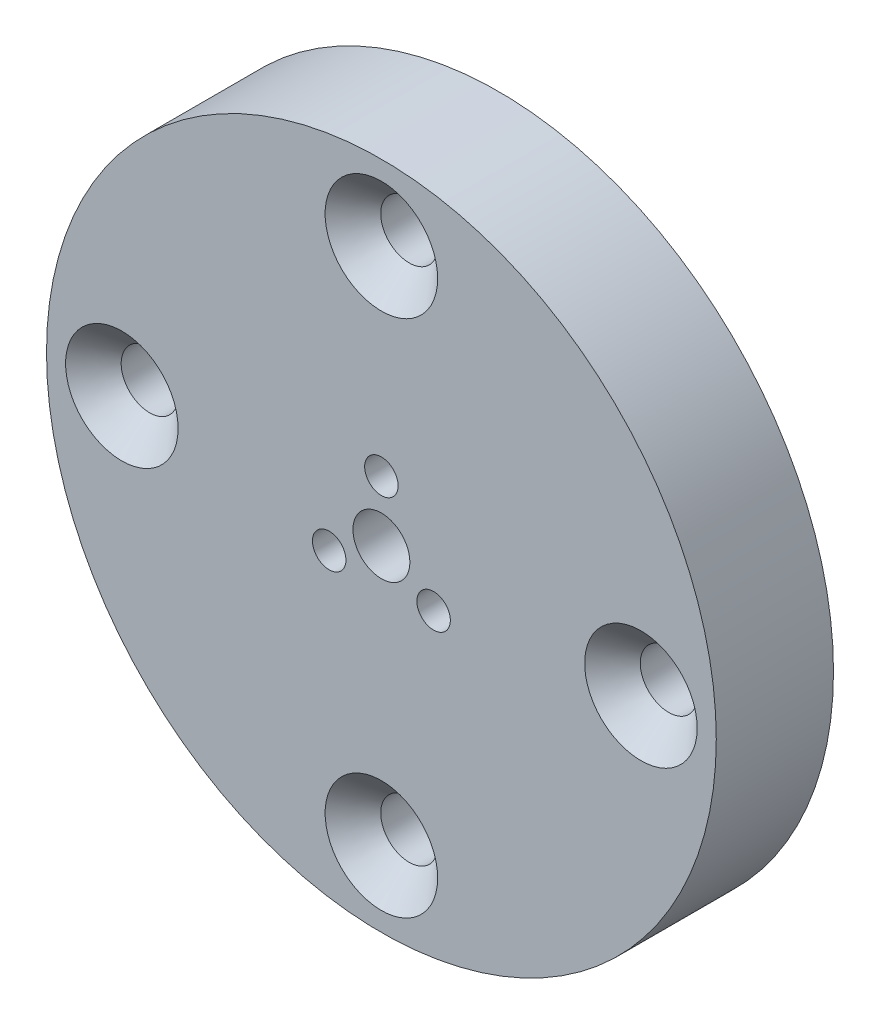
SolidWorks part; units mm, degrees
material "7075-O (SS)"
ref_plane "Front" through (0, 0, 0) normal (0, 0, 1) x (1, 0, 0)
ref_plane "Top" through (0, 0, 0) normal (0, 1, 0) x (1, 0, 0)
ref_plane "Right" through (0, 0, 0) normal (1, 0, 0) x (0, 0, -1)
sketch "Croquis1" plane through (0, 0, 0) normal (0, 0, 1) x (1, 0, 0)
  line L0 (0, -2.75) -> (0, 2.75) construction
  line L1 (2.75, 0) -> (-2.75, 0) construction
  circle A0 centre (0, 0) radius 20
  circle A1 centre (0, 3.6) radius 1
  circle A2 centre (3.1177, -1.8) radius 1
  circle A3 centre (-3.1177, -1.8) radius 1
  dimension "D1" = 40
  dimension "D2" = 2
  dimension "D3" = 3.6
  dimension "D4" = 3
extrude "Saliente-Extruir1" add sketch "Croquis1" along normal blind 7
hole_wizard "Refrentado para tornillo tapón con cabeza plana de clavija de M31" positions "Croquis2" profile "Croquis4" countersink size "M3" standard "Ansi Metric" end condition up to next
sketch "Croquis2" plane through (0, 0, 7) normal (0, 0, 1) x (1, 0, 0)
  line L0 (0, -2.75) -> (0, 2.75) construction
  point P0 (0, 15.5)
  point P12 (15.5, 0)
  point P13 (0, -15.5)
  point P14 (-15.5, 0)
  dimension "D1" = 4
sketch "Croquis4" plane through (0, 15.5, 7) normal (1, 0, 0) x (0, -1, 0)
  line L0 (0, 0) -> (0, 7)
  line L1 (0, 7) -> (1.7, 7)
  line L2 (1.7, 7) -> (1.7, 1.66)
  line L3 (1.7, 1.66) -> (3.36, 0)
  line L5 (3.36, 0) -> (0, 0)
  line L6 (-1.7, 1.66) -> (-3.36, 0) construction
  line L11 (0, -6.35) -> (0, 107.95) construction
  dimension "Diámetro de taladro hasta el siguiente" = 3.4
  dimension "Profundidad de taladro hasta el siguiente" = 7
  dimension "Diámetro de avellanado cercano" = 6.72
  dimension "Ángulo de avellanado cercano" = 90
hole_wizard "Taladro de margen para M31" positions "Croquis5" profile "Croquis7" hole size "M3" standard "Ansi Metric" end condition up to next
sketch "Croquis5" plane through (0, 0, 7) normal (0, 0, 1) x (1, 0, 0)
  point P0 (0, 0)
sketch "Croquis7" plane through (0, 0, 7) normal (1, 0, 0) x (0, -1, 0)
  line L0 (0, 0) -> (0, 7)
  line L1 (0, 7) -> (1.7, 7)
  line L2 (1.7, 7) -> (1.7, 0)
  line L5 (1.7, 0) -> (0, 0)
  line L11 (0, -6.35) -> (0, 107.95) construction
  dimension "Diámetro de taladro hasta el siguiente" = 3.4
  dimension "Profundidad de taladro hasta el siguiente" = 7
sketch "Croquis8" plane through (0, 0, 0) normal (0, 0, -1) x (-1, 0, 0)
  circle A0 centre (0, 0) radius 5
  dimension "D1" = 10
extrude "Cortar-Extruir1" cut sketch "Croquis8" against normal blind 3
